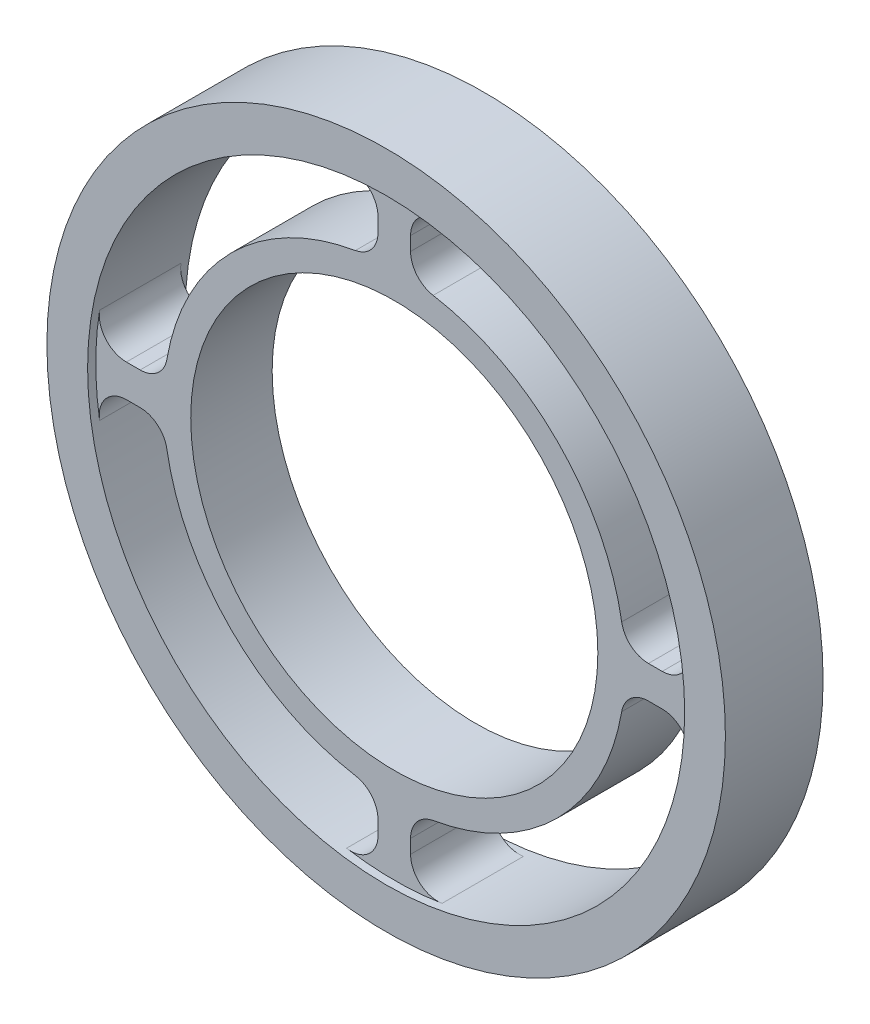
SolidWorks part; units mm, degrees
ref_plane "前视基准面" through (0, 0, 0) normal (0, 0, 1) x (1, 0, 0)
ref_plane "上视基准面" through (0, 0, 0) normal (0, 1, 0) x (1, 0, 0)
ref_plane "右视基准面" through (0, 0, 0) normal (1, 0, 0) x (0, 0, -1)
other "Configuration Table"
sketch "草图1" plane through (0, 0, 0) normal (0, 0, 1) x (1, 0, 0)
  circle A0 centre (0, 0) radius 7.5
  circle A1 centre (0, 0) radius 8.5
  dimension "D1" = 15
  dimension "D2" = 17
extrude "凸台-拉伸1" add sketch "草图1" along normal blind 3.6
sketch "草图2" plane through (0, 0, 3.6) normal (0, 0, 1) x (1, 0, 0)
  circle A0 centre (0, 0) radius 12.5
  circle A1 centre (0, 0) radius 11
  circle A2 centre (0, 0) radius 7.5 construction
  circle A3 centre (0, 0) radius 8.5
  circle A4 centre (0, 0) radius 8.5
  circle A5 centre (0, 0) radius 7.5
  dimension "D1" = 22
  dimension "D2" = 25
  dimension "D3" = 0
extrude "凸台-拉伸2" add sketch "草图2" against normal blind 3.6 separate body contours A0 A1
ref_plane "基准面1" through (0, 0, 3.3) normal (0, 0, 1) x (1, 0, 0)
sketch "草图4" plane through (0, 0, 3.3) normal (0, 0, 1) x (1, 0, 0)
  line L0 (-11, 0) -> (11, 0) construction
  line L1 (0.6, -8) -> (0.6, -11.5)
  line L2 (8, 0.6) -> (11.5, 0.6)
  line L3 (8, 0.6) -> (8, -0.6)
  line L4 (8, -0.6) -> (11.5, -0.6)
  line L5 (11.5, 0.6) -> (11.5, -0.6)
  line L6 (-0.6, -8) -> (-0.6, -11.5)
  line L7 (0.6, -8) -> (-0.6, -8)
  line L8 (0.6, -11.5) -> (-0.6, -11.5)
  line L9 (-8, -0.6) -> (-11.5, -0.6)
  line L10 (-8, 0.6) -> (-11.5, 0.6)
  line L11 (-8, -0.6) -> (-8, 0.6)
  line L12 (-11.5, -0.6) -> (-11.5, 0.6)
  line L13 (-0.6, 8) -> (-0.6, 11.5)
  line L14 (0.6, 8) -> (0.6, 11.5)
  line L15 (-0.6, 8) -> (0.6, 8)
  line L16 (-0.6, 11.5) -> (0.6, 11.5)
  circle A0 centre (0, 0) radius 8.5 construction
  circle A1 centre (0, 0) radius 8.5
  circle A2 centre (0, 0) radius 11 construction
  circle A3 centre (0, 0) radius 11
  point P26 (0, 0)
  dimension "D1" = 1.2
  dimension "D2" = 0.5
  dimension "D3" = 8
  dimension "D4" = 4
extrude "凸台-拉伸3" add sketch "草图4" against normal blind 3 contours L14 A3 L13 A1 | A3 L0 A1 L10 | L6 A3 L1 A1 | A1 L0 A3 L2 | L3 L0 A1 L2 | A3 L4 L5 L2 | L0 A1 L4 A3 | L0 L3 L4 A1 | A3 L6 L8 L1 | L6 A1 L1 L7 | A3 L10 L12 L9 | L0 A3 L9 A1 | L0 A1 L9 L11 | A1 L0 L11 L10 | A3 L14 L16 L13 | L14 A1 L13 L15
fillet "圆角1" radius 1 16 edges at (-8.4788, -0.6, 1.8) (-10.9836, -0.6, 1.8) (-10.9836, 0.6, 1.8) (-8.4788, 0.6, 1.8) (-0.6, 8.4788, 1.8) (-0.6, 10.9836, 1.8) (0.6, 10.9836, 1.8) (0.6, 8.4788, 1.8) (10.9836, 0.6, 1.8) (8.4788, 0.6, 1.8) (10.9836, -0.6, 1.8) (8.4788, -0.6, 1.8) (0.6, -8.4788, 1.8) (0.6, -10.9836, 1.8) (-0.6, -10.9836, 1.8) (-0.6, -8.4788, 1.8)
sketch "草图5" plane through (0, 0, 3.6) normal (0, 0, 1) x (1, 0, 0)
  circle A0 centre (0, 0) radius 7.5 construction
  circle A1 centre (0, 0) radius 8.5
  circle A2 centre (0, 0) radius 8.5
  circle A3 centre (0, 0) radius 7.5
  dimension "D1" = 0
extrude "切除-拉伸1" cut sketch "草图5" against normal blind 0.3
sketch "草图6" plane through (0, 0, 0) normal (0, 0, -1) x (-1, 0, 0)
  circle A0 centre (0, 0) radius 7.5 construction
  circle A1 centre (0, 0) radius 8.5
  circle A2 centre (0, 0) radius 8.5
  circle A3 centre (0, 0) radius 7.5
  dimension "D1" = 0
extrude "切除-拉伸2" cut sketch "草图6" against normal blind 0.3
